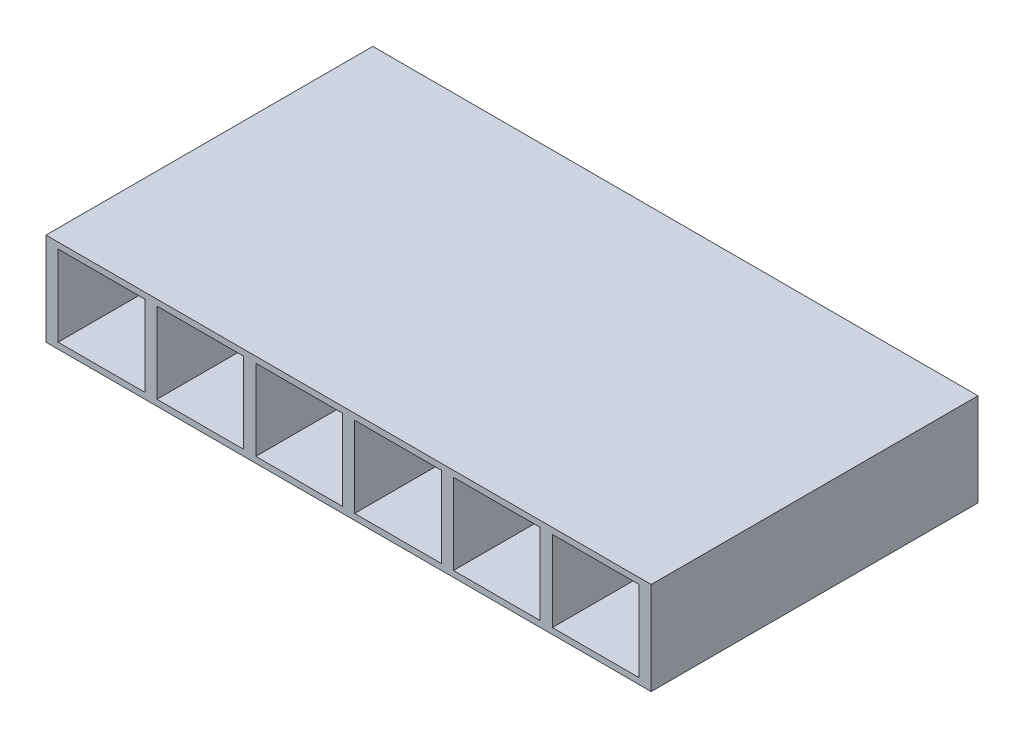
SolidWorks part; units mm, degrees
ref_plane "Plan de face" through (0, 0, 0) normal (0, 0, 1) x (1, 0, 0)
ref_plane "Plan de dessus" through (0, 0, 0) normal (0, 1, 0) x (1, 0, 0)
ref_plane "Plan de droite" through (0, 0, 0) normal (1, 0, 0) x (0, 0, -1)
sketch "Esquisse1" plane through (0, 0, 0) normal (0, 0, 1) x (1, 0, 0)
  line L0 (-2.6631, -1) -> (-2.6631, 1)
  line L1 (-7.5631, -1.15) -> (7.4369, -1.15)
  line L2 (-7.5631, -1.15) -> (-7.5631, 1.15)
  line L3 (-7.5631, 1.15) -> (7.4369, 1.15)
  line L4 (7.4369, -1.15) -> (7.4369, 1.15)
  line L5 (-7.5631, -1.15) -> (-5.1131, -0.7775) construction
  line L6 (-7.5631, 1.15) -> (-5.1131, 0.7775) construction
  line L7 (-7.2631, -1) -> (-5.1131, -1)
  line L8 (-7.2631, -1) -> (-7.2631, 1)
  line L9 (-7.2631, 1) -> (-5.1131, 1)
  line L10 (-5.1131, -1) -> (-5.1131, 1)
  line L11 (-7.2631, -1) -> (-5.1131, 1) construction
  line L12 (-7.2631, 1) -> (-5.1131, -1) construction
  line L13 (-4.8131, -1) -> (-4.8131, 1)
  line L14 (-4.8131, 1) -> (-2.6631, 1)
  line L15 (-4.8131, -1) -> (-2.6631, -1)
  line L16 (-0.2131, -1) -> (-0.2131, 1)
  line L17 (-2.3631, -1) -> (-2.3631, 1)
  line L18 (-2.3631, 1) -> (-0.2131, 1)
  line L19 (-2.3631, -1) -> (-0.2131, -1)
  line L20 (2.2369, -1) -> (2.2369, 1)
  line L21 (0.0869, -1) -> (0.0869, 1)
  line L22 (0.0869, 1) -> (2.2369, 1)
  line L23 (0.0869, -1) -> (2.2369, -1)
  line L24 (4.6869, -1) -> (4.6869, 1)
  line L25 (2.5369, -1) -> (2.5369, 1)
  line L26 (2.5369, 1) -> (4.6869, 1)
  line L27 (2.5369, -1) -> (4.6869, -1)
  line L28 (7.1369, -1) -> (7.1369, 1)
  line L29 (4.9869, -1) -> (4.9869, 1)
  line L30 (4.9869, 1) -> (7.1369, 1)
  line L31 (4.9869, -1) -> (7.1369, -1)
  point P0 (0, 0)
  point P6 (-6.1881, 0)
  dimension "D1" = 15
  dimension "D2" = 2.3
  dimension "D3" = 2
  dimension "D4" = 2.15
  dimension "D5" = 0.3
  dimension "D6" = 6
extrude "Boss.-Extru.1" add sketch "Esquisse1" along normal blind 8.1
